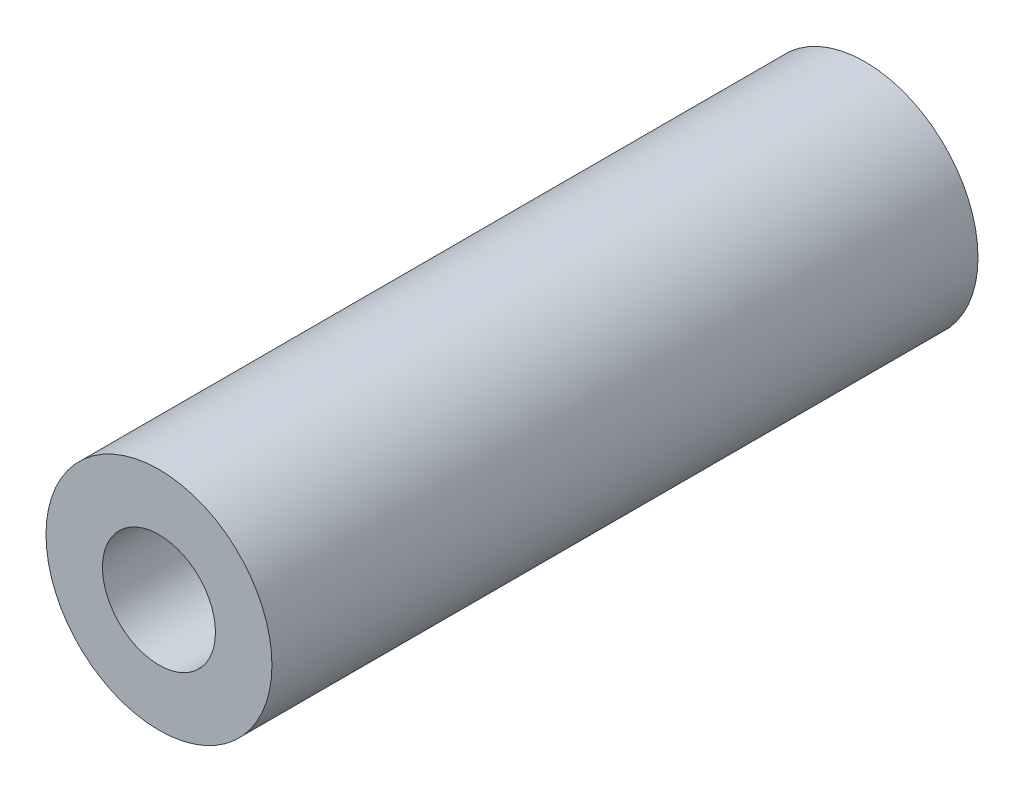
SolidWorks part; units mm, degrees
ref_plane "前视基准面" through (0, 0, 0) normal (0, 0, 1) x (1, 0, 0)
ref_plane "上视基准面" through (0, 0, 0) normal (0, 1, 0) x (1, 0, 0)
ref_plane "右视基准面" through (0, 0, 0) normal (1, 0, 0) x (0, 0, -1)
sketch "草图1" plane through (0, 0, 0) normal (0, 0, 1) x (1, 0, 0)
  circle A0 centre (0, 0) radius 4
  circle A1 centre (0, 0) radius 2
  dimension "D1" = 4
  dimension "D2" = 8
extrude "凸台-拉伸1" add sketch "草图1" along normal mid plane 25
